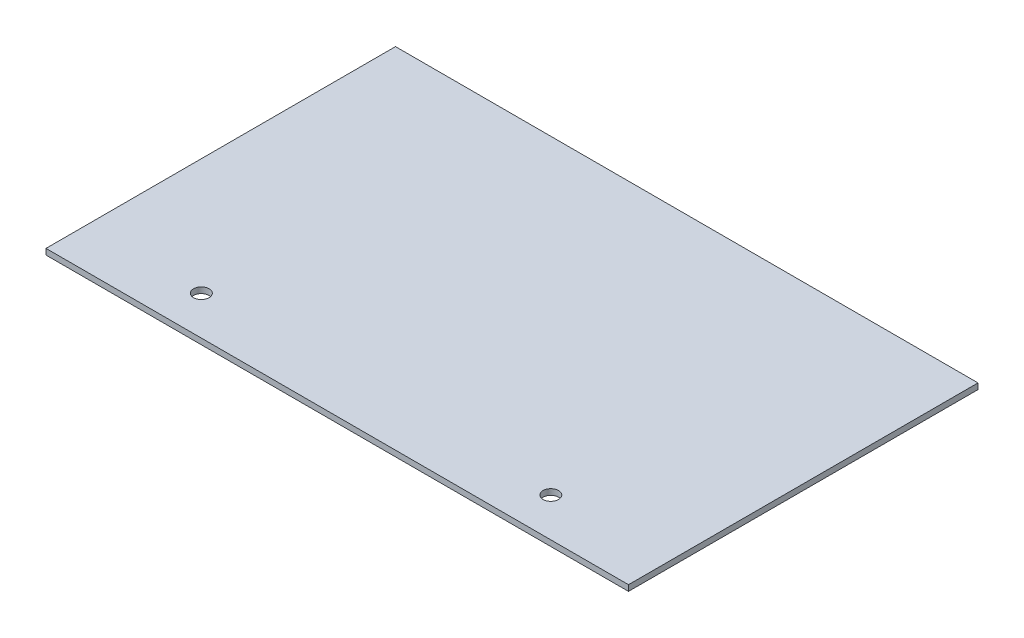
SolidWorks part; units mm, degrees
material "环氧树脂,未充填"
ref_plane "前视基准面" through (0, 0, 0) normal (0, 0, 1) x (1, 0, 0)
ref_plane "上视基准面" through (0, 0, 0) normal (0, 1, 0) x (1, 0, 0)
ref_plane "右视基准面" through (0, 0, 0) normal (1, 0, 0) x (0, 0, -1)
sketch "草图1" plane through (0, 0, 0) normal (0, 1, 0) x (1, 0, 0)
  line L1 (0, 0) -> (300, 0)
  line L2 (0, 0) -> (0, -180)
  line L3 (0, -180) -> (300, -180)
  line L4 (300, 0) -> (300, -180)
  dimension "D1" = 300
  dimension "D2" = 180
extrude "凸台-拉伸1" add sketch "草图1" along normal blind 3
sketch "草图2" plane through (0, 3, 0) normal (0, 1, 0) x (1, 0, 0)
  line L0 (300, -180) -> (300, 0) construction
  line L1 (0, 0) -> (0, -180) construction
  line L2 (0, -180) -> (300, -180) construction
  circle A0 centre (60, -160) radius 4
  circle A1 centre (240, -160) radius 4
  dimension "D1" = 8
  dimension "D2" = 8
  dimension "D3" = 60
  dimension "D4" = 60
  dimension "D5" = 20
  dimension "D6" = 20
extrude "切除-拉伸1" cut sketch "草图2" against normal through all
